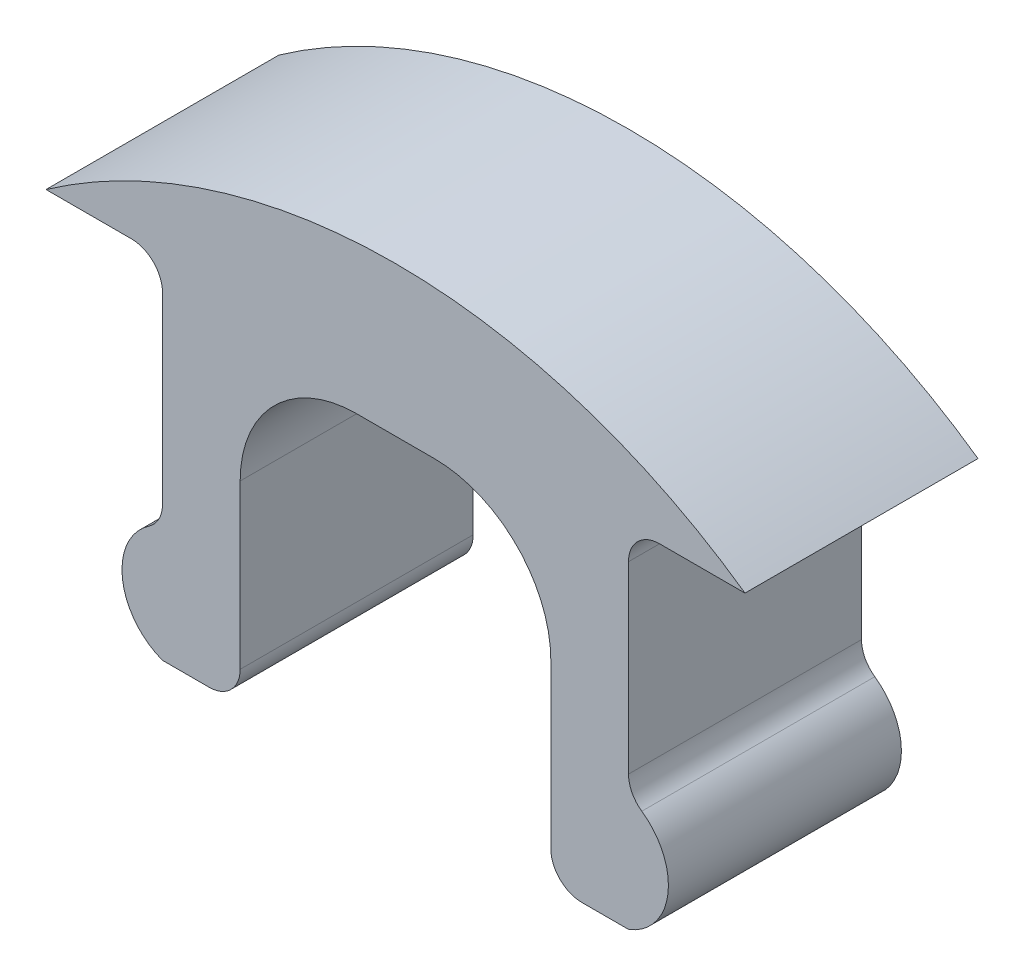
SolidWorks part; units mm, degrees
ref_plane "Płaszczyzna przednia" through (0, 0, 0) normal (0, 0, 1) x (1, 0, 0)
ref_plane "Płaszczyzna górna" through (0, 0, 0) normal (0, 1, 0) x (1, 0, 0)
ref_plane "Płaszczyzna prawa" through (0, 0, 0) normal (1, 0, 0) x (0, 0, -1)
sketch "Szkic1" plane through (0, 0, 0) normal (0, 0, 1) x (1, 0, 0)
  line L0 (0, 3) -> (-1.5, 3)
  line L2 (0, 0) -> (0, 3)
  line L4 (6, -0.0059) -> (6, 3)
  line L5 (6, 3) -> (7.5, 3)
  line L7 (0, -1.5) -> (1, -1.5)
  line L8 (1, -1.5) -> (1, 2.5)
  line L9 (1, 2.5) -> (5, 2.5)
  line L10 (5, 2.5) -> (5, -1.5)
  line L11 (5, -1.5) -> (6, -1.5)
  arc A0 (-1.5, 3) -> (7.5, 3) centre (3, -3.3917) cw
  arc A1 (0, -1.5) -> (0, 0) centre (0.2784, -0.75) cw
  arc A2 (6, -0.0059) -> (6, -1.5) centre (5.7138, -0.753) cw
extrude "Dodanie-wyciągnięcie1" add sketch "Szkic1" along normal blind 3
fillet "Zaokrąglenie2" radius 0.4 6 edges at (0, 0, 1.5) (6, -0.0059, 1.5) (6, 3, 1.5) (0, 3, 1.5) (1, -1.5, 1.5) (5, -1.5, 1.5)
fillet "Zaokrąglenie3" radius 1.5 2 edges at (5, 2.5, 1.5) (1, 2.5, 1.5)
